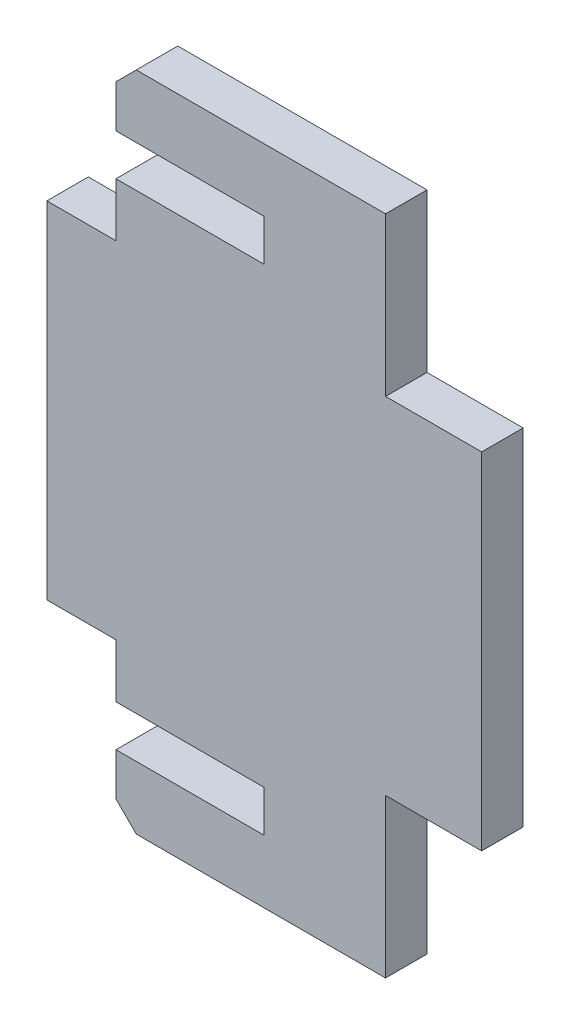
SolidWorks part; units mm, degrees
ref_plane "Front" through (0, 0, 0) normal (0, 0, 1) x (1, 0, 0)
ref_plane "Top" through (0, 0, 0) normal (0, 1, 0) x (1, 0, 0)
ref_plane "Right" through (0, 0, 0) normal (1, 0, 0) x (0, 0, -1)
sketch "Sketch1" plane through (0, 0, 0) normal (0, 0, 1) x (1, 0, 0)
  line L0 (628.8074, -34.821) -> (628.8074, -23.3848)
  line L1 (609.3074, -30.2699) -> (609.3074, -33.3523)
  line L2 (610.7761, -34.821) -> (628.8074, -34.821)
  line L3 (610.7761, -34.821) -> (609.3074, -33.3523)
  line L4 (604.3074, -10.8848) -> (635.7607, -10.8848) construction
  line L5 (620.0066, 5.5003) -> (620.0024, 8.5003)
  line L6 (635.7607, 1.6152) -> (628.8074, 1.6152)
  line L7 (609.3074, -27.2699) -> (620.0066, -27.2699)
  line L8 (620.0024, -30.2699) -> (609.3074, -30.2699)
  line L9 (609.3074, 1.6152) -> (609.3074, 5.5003)
  line L10 (604.3074, 1.6152) -> (604.3074, -23.3848)
  line L11 (604.3074, -23.3848) -> (609.3074, -23.3848)
  line L12 (609.3074, -23.3848) -> (609.3074, -27.2699)
  line L13 (604.3074, 1.6152) -> (609.3074, 1.6152)
  line L14 (620.0024, 8.5003) -> (609.3074, 8.5003)
  line L15 (609.3074, 5.5003) -> (620.0066, 5.5003)
  line L16 (610.7761, 13.0515) -> (609.3074, 11.5827)
  line L17 (610.7761, 13.0515) -> (628.8074, 13.0515)
  line L18 (635.7607, -23.3848) -> (635.7607, 1.6152)
  line L19 (635.7607, -23.3848) -> (628.8074, -23.3848)
  line L20 (620.0066, -27.2699) -> (620.0024, -30.2699)
  line L21 (609.3074, 8.5003) -> (609.3074, 11.5827)
  line L22 (628.8074, 13.0515) -> (628.8074, 1.6152)
  dimension "D1" = 25
  dimension "D2" = 3
  dimension "D3" = 12.5
  dimension "D4" = 19.5
  dimension "D5" = 3.8851
  dimension "D6" = 6.9533
  dimension "D7" = 5
extrude "Base-Extrude" add sketch "Sketch1" against normal blind 3
